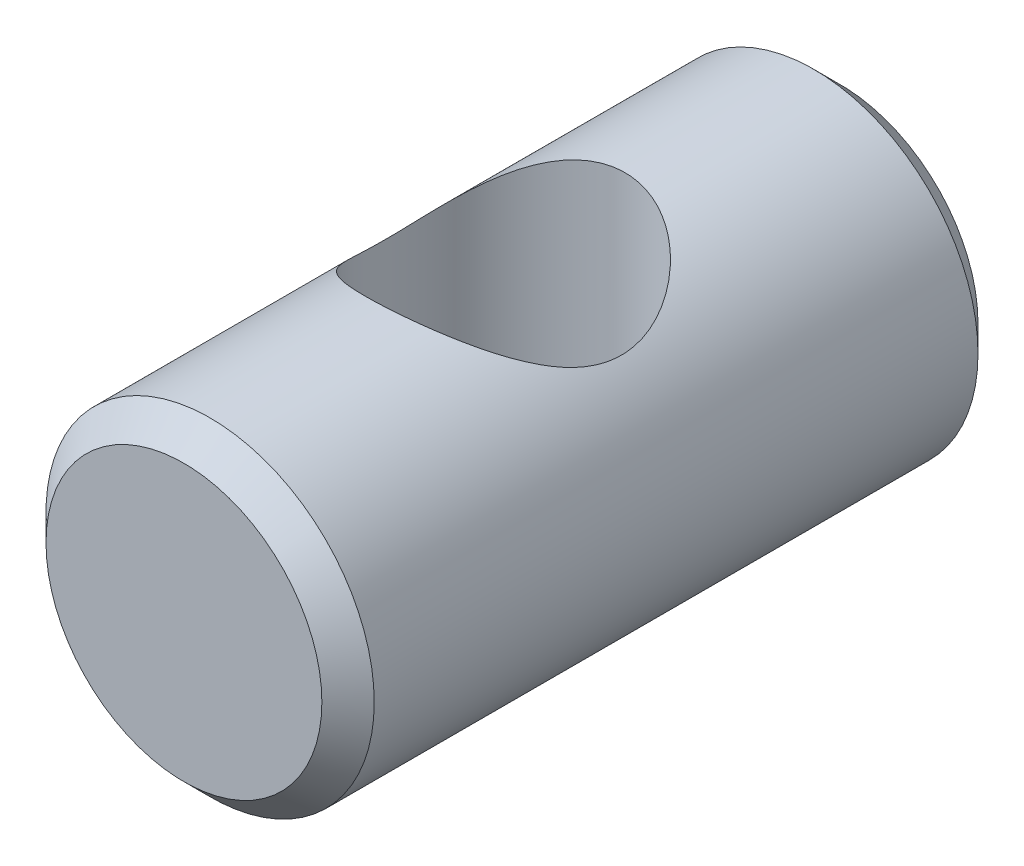
SolidWorks part; units mm, degrees
material "Alloy Steel"
ref_plane "Front Plane" through (0, 0, 0) normal (0, 0, 1) x (1, 0, 0)
ref_plane "Top Plane" through (0, 0, 0) normal (0, 1, 0) x (1, 0, 0)
ref_plane "Right Plane" through (0, 0, 0) normal (1, 0, 0) x (0, 0, -1)
sketch "Sketch2" plane through (0, 0, 0) normal (0, 0, 1) x (1, 0, 0)
  circle A0 centre (0, 0) radius 4.765
  dimension "D1" = 9.53
extrude "Boss-Extrude1" add sketch "Sketch2" along normal mid plane 19.05
sketch "Sketch3" plane through (0, 0, 0) normal (0, 1, 0) x (1, 0, 0)
  circle A0 centre (-0.25, 0) radius 3.43
  dimension "D1" = 6.86
  dimension "D2" = 0.25
extrude "Cut-Extrude1" cut sketch "Sketch3" against normal through all and the other way through all
chamfer "Chamfer1" distance 0.76 2 edges at (4.765, 0, -9.525) (4.765, 0, 9.525)
